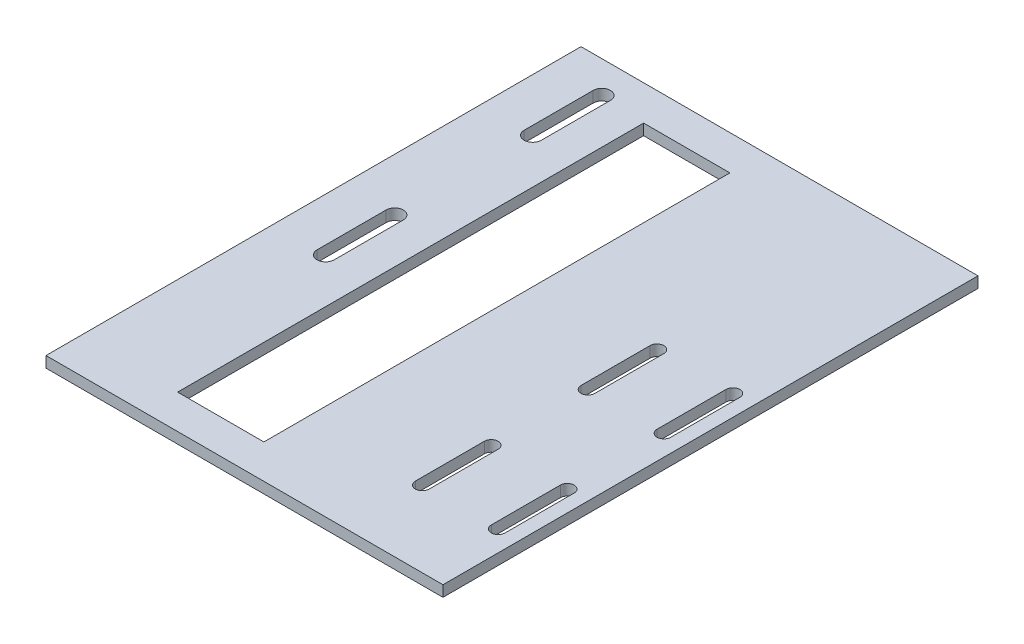
SolidWorks part; units mm, degrees
ref_plane "Front Plane" through (0, 0, 0) normal (0, 0, 1) x (1, 0, 0)
ref_plane "Top Plane" through (0, 0, 0) normal (0, 1, 0) x (1, 0, 0)
ref_plane "Right Plane" through (0, 0, 0) normal (1, 0, 0) x (0, 0, -1)
sketch "Sketch1" plane through (0, 0, 0) normal (0, 1, 0) x (1, 0, 0)
  line L0 (-19.0866, 15.0395) -> (5.9134, 15.0395) construction
  line L1 (67.6743, 92.6518) -> (67.6743, -62.3482)
  line L2 (67.6743, -62.3482) -> (-47.3257, -62.3482)
  line L3 (-47.3257, -62.3482) -> (-47.3257, -27.0446)
  line L4 (-6.5866, 75.2355) -> (-6.5866, -88.6335) construction
  line L5 (67.6743, 92.6518) -> (-47.3257, 92.6518)
  line L6 (-47.3257, -27.0446) -> (-47.3257, 92.6518)
  line L7 (-19.0866, 82.5395) -> (5.9134, 82.5395)
  line L8 (-19.0866, 82.5395) -> (-19.0866, -52.4605)
  line L9 (-19.0866, -52.4605) -> (5.9134, -52.4605)
  line L10 (5.9134, 82.5395) -> (5.9134, -52.4605)
  line L11 (50.6743, -62.3482) -> (50.6743, 92.6518) construction
  line L12 (-32.0866, 63.4274) -> (-32.0866, 83.4274) construction
  line L13 (-34.5866, 63.4274) -> (-34.5866, 83.4274)
  line L14 (-29.5866, 63.4274) -> (-29.5866, 83.4274)
  line L15 (-32.0866, 3.4274) -> (-32.0866, 23.4274) construction
  line L16 (-34.5866, 3.4274) -> (-34.5866, 23.4274)
  line L17 (-29.5866, 3.4274) -> (-29.5866, 23.4274)
  line L18 (61.6743, 7.6518) -> (61.6743, 27.6518) construction
  line L19 (59.6743, 7.6518) -> (59.6743, 27.6518)
  line L20 (63.6743, 7.6518) -> (63.6743, 27.6518)
  line L21 (61.6743, -40.3482) -> (61.6743, -20.3482) construction
  line L22 (59.6743, -40.3482) -> (59.6743, -20.3482)
  line L23 (63.6743, -40.3482) -> (63.6743, -20.3482)
  line L24 (39.6743, 7.6518) -> (39.6743, 27.6518) construction
  line L25 (41.6743, 7.6518) -> (41.6743, 27.6518)
  line L26 (37.6743, 7.6518) -> (37.6743, 27.6518)
  line L27 (39.6743, -40.3482) -> (39.6743, -20.3482) construction
  line L28 (41.6743, -40.3482) -> (41.6743, -20.3482)
  line L29 (37.6743, -40.3482) -> (37.6743, -20.3482)
  circle A2 centre (-32.0866, 13.4274) radius 2 construction
  circle A3 centre (-32.0866, 73.4274) radius 1.7 construction
  arc A10 (-34.5866, 63.4274) -> (-29.5866, 63.4274) centre (-32.0866, 63.4274) ccw
  arc A11 (-29.5866, 83.4274) -> (-34.5866, 83.4274) centre (-32.0866, 83.4274) ccw
  arc A12 (-34.5866, 3.4274) -> (-29.5866, 3.4274) centre (-32.0866, 3.4274) ccw
  arc A13 (-29.5866, 23.4274) -> (-34.5866, 23.4274) centre (-32.0866, 23.4274) ccw
  arc A14 (59.6743, 7.6518) -> (63.6743, 7.6518) centre (61.6743, 7.6518) ccw
  arc A15 (63.6743, 27.6518) -> (59.6743, 27.6518) centre (61.6743, 27.6518) ccw
  arc A16 (59.6743, -40.3482) -> (63.6743, -40.3482) centre (61.6743, -40.3482) ccw
  arc A17 (63.6743, -20.3482) -> (59.6743, -20.3482) centre (61.6743, -20.3482) ccw
  arc A18 (41.6743, 7.6518) -> (37.6743, 7.6518) centre (39.6743, 7.6518) cw
  arc A19 (37.6743, 27.6518) -> (41.6743, 27.6518) centre (39.6743, 27.6518) cw
  arc A20 (41.6743, -40.3482) -> (37.6743, -40.3482) centre (39.6743, -40.3482) cw
  arc A21 (37.6743, -20.3482) -> (41.6743, -20.3482) centre (39.6743, -20.3482) cw
  point P6 (39.6743, 17.6518)
  point P31 (-32.0866, 73.4274)
  point P37 (-32.0866, 13.4274)
  point P43 (61.6743, 17.6518)
  point P49 (61.6743, -30.3482)
  point P56 (39.6743, -30.3482)
  dimension "D11" = 2.5
  dimension "D13" = 13
  dimension "D14" = 2.5
  dimension "D16" = 2
  dimension "D17" = 2
  dimension "D1" = 25
  dimension "D6" = 115
  dimension "D7" = 135
  dimension "D9" = 155
  dimension "D10" = 17
  dimension "D12" = 20
  dimension "D15" = 20
  dimension "D18" = 20
  dimension "D19" = 20
extrude "Boss-Extrude1" add sketch "Sketch1" along normal blind 3.175
